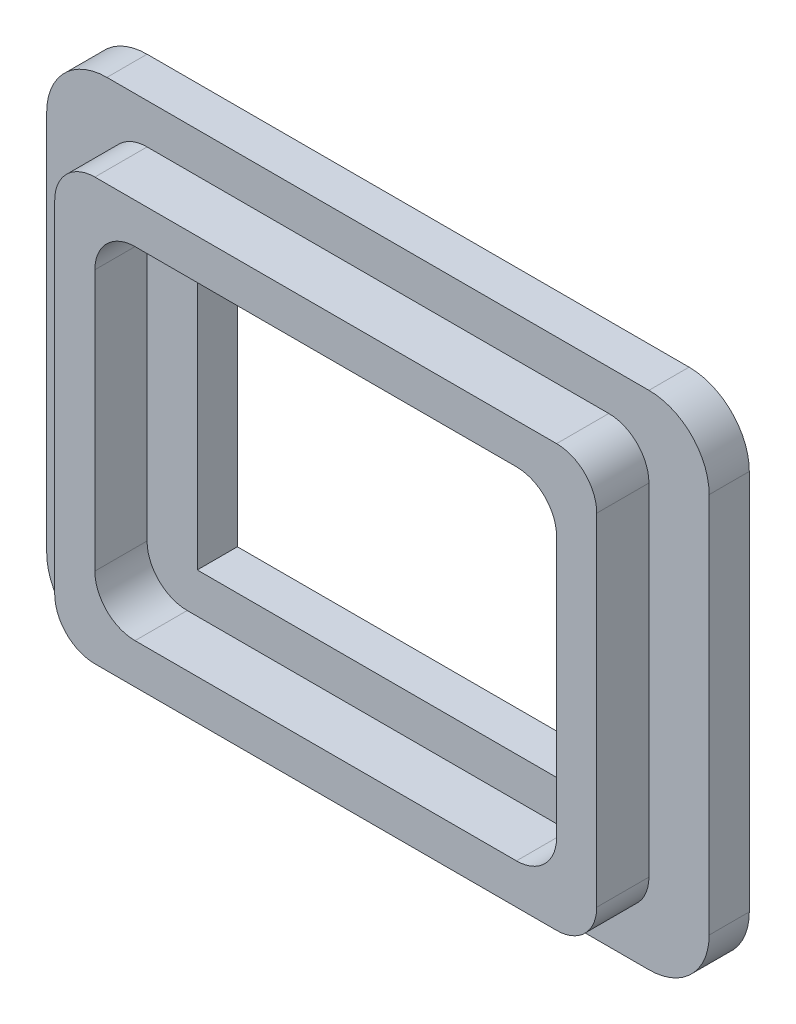
SolidWorks part; units mm, degrees
ref_plane "Ön Düzlem" through (0, 0, 0) normal (0, 0, 1) x (1, 0, 0)
ref_plane "Üst Düzlem" through (0, 0, 0) normal (0, 1, 0) x (1, 0, 0)
ref_plane "Sağ Düzlem" through (0, 0, 0) normal (1, 0, 0) x (0, 0, -1)
sketch "Çizim1" plane through (0, 0, 0) normal (0, 0, 1) x (1, 0, 0)
  line L1 (-13.5, 12.5) -> (13.5, 12.5)
  line L2 (-16.5, 9.5) -> (-16.5, -9.5)
  line L3 (-13.5, -12.5) -> (13.5, -12.5)
  line L4 (16.5, 9.5) -> (16.5, -9.5)
  line L5 (-16.5, 12.5) -> (16.5, -12.5) construction
  line L6 (-16.5, -12.5) -> (16.5, 12.5) construction
  arc A0 (13.5, 12.5) -> (16.5, 9.5) centre (13.5, 9.5) cw
  arc A1 (16.5, -9.5) -> (13.5, -12.5) centre (13.5, -9.5) cw
  arc A2 (-13.5, -12.5) -> (-16.5, -9.5) centre (-13.5, -9.5) cw
  arc A3 (-16.5, 9.5) -> (-13.5, 12.5) centre (-13.5, 9.5) cw
  point P0 (0, 0)
  dimension "D3" = 3
  dimension "D1" = 33
  dimension "D2" = 25
extrude "Yükseklik-Ekstrüzyon1" add sketch "Çizim1" along normal blind 2
sketch "Çizim2" plane through (0, 0, 2) normal (0, 0, 1) x (1, 0, 0)
  line L0 (0, 12.5) -> (0, -12.5) construction
  line L1 (13.5, 12.5) -> (-13.5, 12.5) construction
  line L2 (-13.5, -12.5) -> (13.5, -12.5) construction
  line L3 (-16.5, 0) -> (16.5, 0) construction
  line L4 (-16.5, 9.5) -> (-16.5, -9.5) construction
  line L5 (16.5, -9.5) -> (16.5, 9.5) construction
  line L7 (-11.5, 10.5) -> (11.5, 10.5)
  line L8 (-13.5, 8.5) -> (-13.5, -8.5)
  line L9 (-11.5, -10.5) -> (11.5, -10.5)
  line L10 (13.5, 8.5) -> (13.5, -8.5)
  line L11 (-13.5, 10.5) -> (13.5, -10.5) construction
  line L12 (-13.5, -10.5) -> (13.5, 10.5) construction
  line L13 (-9.5, 8.5) -> (9.5, 8.5)
  line L14 (-11.5, 6.5) -> (-11.5, -6.5)
  line L15 (-9.5, -8.5) -> (9.5, -8.5)
  line L16 (11.5, 6.5) -> (11.5, -6.5)
  line L17 (-11.5, 8.5) -> (11.5, -8.5) construction
  line L18 (-11.5, -8.5) -> (11.5, 8.5) construction
  arc A0 (9.5, 8.5) -> (11.5, 6.5) centre (9.5, 6.5) cw
  arc A1 (11.5, 10.5) -> (13.5, 8.5) centre (11.5, 8.5) cw
  arc A2 (11.5, -6.5) -> (9.5, -8.5) centre (9.5, -6.5) cw
  arc A3 (13.5, -8.5) -> (11.5, -10.5) centre (11.5, -8.5) cw
  arc A4 (-9.5, -8.5) -> (-11.5, -6.5) centre (-9.5, -6.5) cw
  arc A5 (-11.5, -10.5) -> (-13.5, -8.5) centre (-11.5, -8.5) cw
  arc A6 (-11.5, 6.5) -> (-9.5, 8.5) centre (-9.5, 6.5) cw
  arc A7 (-13.5, 8.5) -> (-11.5, 10.5) centre (-11.5, 8.5) cw
  point P12 (0, 0)
  point P18 (0, 0)
  dimension "D5" = 2
  dimension "D1" = 27
  dimension "D2" = 21
  dimension "D3" = 23
  dimension "D4" = 17
extrude "Yükseklik-Ekstrüzyon2" add sketch "Çizim2" along normal blind 2.6
sketch "Çizim3" plane through (0, 0, 2) normal (0, 0, 1) x (1, 0, 0)
  line L1 (-9, 6.5) -> (9, 6.5)
  line L2 (-9, 6.5) -> (-9, -6.5)
  line L3 (-9, -6.5) -> (9, -6.5)
  line L4 (9, 6.5) -> (9, -6.5)
  line L5 (-9, 6.5) -> (9, -6.5) construction
  line L6 (-9, -6.5) -> (9, 6.5) construction
  point P0 (0, 0)
  dimension "D1" = 18
  dimension "D2" = 13
extrude "Kes-Ekstrüzyon1" cut sketch "Çizim3" against normal blind 12
